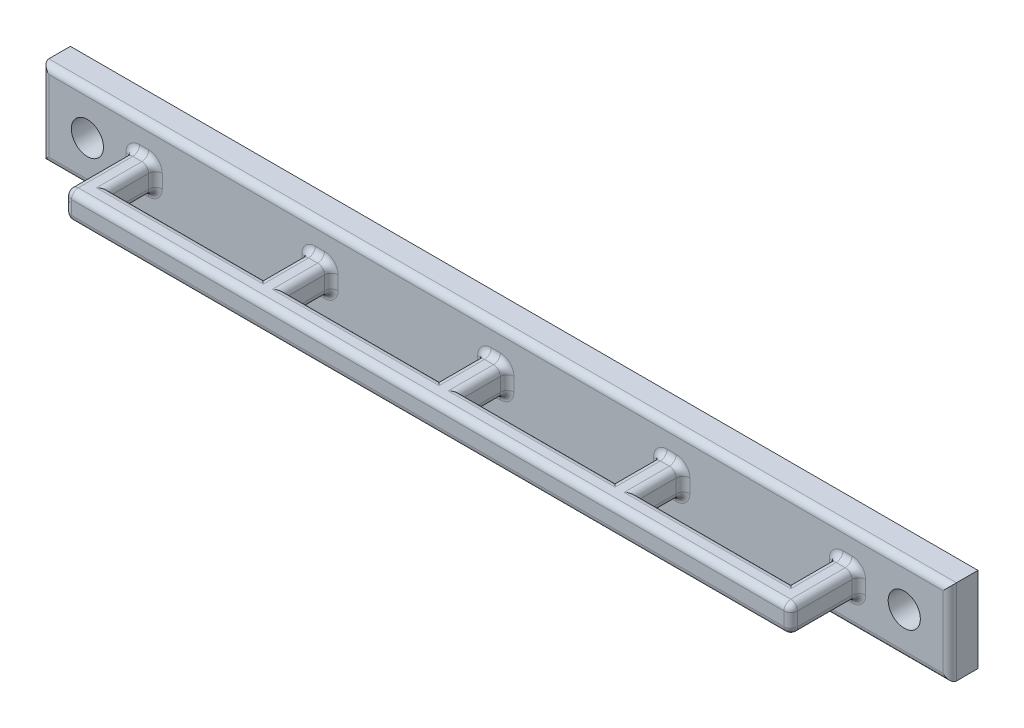
SolidWorks part; units mm, degrees
ref_plane "Front Plane" through (0, 0, 0) normal (0, 0, 1) x (1, 0, 0)
ref_plane "Top Plane" through (0, 0, 0) normal (0, 1, 0) x (1, 0, 0)
ref_plane "Right Plane" through (0, 0, 0) normal (1, 0, 0) x (0, 0, -1)
sketch "Sketch2" plane through (0, 0, 0) normal (0, 0, 1) x (1, 0, 0)
  line L1 (0, 0) -> (101.6, 0)
  line L2 (0, 0) -> (0, 9.525)
  line L3 (0, 9.525) -> (101.6, 9.525)
  line L4 (101.6, 0) -> (101.6, 9.525)
  dimension "D1" = 101.6
  dimension "D2" = 9.525
extrude "Boss-Extrude1" add sketch "Sketch2" along normal blind 3.175
hole_wizard "M3 Clearance Hole1" positions "Sketch3" profile "Sketch4" hole size "M3" standard "ANSI Metric" end condition through all
sketch "Sketch3" plane through (0, 0, 3.175) normal (0, 0, 1) x (1, 0, 0)
  line L0 (0, 9.525) -> (0, 0) construction
  line L1 (101.6, 0) -> (101.6, 9.525) construction
  line L2 (0, 0) -> (101.6, 0) construction
  point P0 (5.08, 4.7625)
  point P2 (96.52, 4.7625)
  dimension "D1" = 5.08
  dimension "D2" = 5.08
  dimension "D3" = 4.7625
sketch "Sketch4" plane through (5.08, 4.7625, 3.175) normal (1, 0, 0) x (0, -1, 0)
  line L0 (0, 0) -> (0, 3.175)
  line L1 (0, 3.175) -> (1.8, 3.175)
  line L2 (1.8, 3.175) -> (1.8, 0)
  line L5 (1.8, 0) -> (0, 0)
  line L11 (0, -6.35) -> (0, 107.95) construction
  dimension "Thru Hole Dia." = 3.6
  dimension "Thru Hole Depth" = 3.175
ref_plane "Plane1" through (0, 4.7625, 0) normal (0, -1, 0) x (-1, 0, 0)
sketch "Sketch5" plane through (0, 4.7625, 0) normal (0, -1, 0) x (-1, 0, 0)
  line L0 (-10.16, -3.175) -> (-10.16, -10.795)
  line L1 (-10.16, -10.795) -> (-91.44, -10.795)
  line L2 (-91.44, -10.795) -> (-91.44, -3.175)
  line L3 (-91.44, -3.175) -> (-88.9, -3.175)
  line L4 (-88.9, -3.175) -> (-88.9, -8.255)
  line L5 (-88.9, -8.255) -> (-71.755, -8.255)
  line L6 (-71.755, -8.255) -> (-71.755, -3.175)
  line L7 (-71.755, -3.175) -> (-69.215, -3.175)
  line L8 (-69.215, -3.175) -> (-69.215, -8.255)
  line L9 (-69.215, -8.255) -> (-52.07, -8.255)
  line L10 (-52.07, -8.255) -> (-52.07, -3.175)
  line L11 (-52.07, -3.175) -> (-49.53, -3.175)
  line L12 (-49.53, -3.175) -> (-49.53, -8.255)
  line L13 (-49.53, -8.255) -> (-32.385, -8.255)
  line L14 (-32.385, -8.255) -> (-32.385, -3.175)
  line L15 (-32.385, -3.175) -> (-29.845, -3.175)
  line L16 (-29.845, -3.175) -> (-29.845, -8.255)
  line L17 (-29.845, -8.255) -> (-12.7, -8.255)
  line L18 (-12.7, -8.255) -> (-12.7, -3.175)
  line L19 (-12.7, -3.175) -> (-10.16, -3.175)
  line L20 (-101.6, -3.175) -> (0, -3.175) construction
  line L21 (0, -3.175) -> (0, 0) construction
  line L22 (-101.6, -3.175) -> (-101.6, 0) construction
  point P2 (-11.43, -3.175)
  dimension "D1" = 10.16
  dimension "D2" = 10.16
  dimension "D3" = 5.08
  dimension "D4" = 2.54
  dimension "D5" = 2.54
extrude "Boss-Extrude2" add sketch "Sketch5" along normal blind 1.524 and the other way blind 1.524
fillet "Fillet1" radius 0.762 56 edges at (88.9, 4.7625, 3.175) (71.755, 4.7625, 3.175) (69.215, 4.7625, 3.175) (52.07, 4.7625, 3.175) (49.53, 4.7625, 3.175) (32.385, 4.7625, 3.175) (29.845, 4.7625, 3.175) (12.7, 4.7625, 3.175) (10.16, 4.7625, 10.795) (10.16, 4.7625, 3.175) (12.7, 6.2865, 5.715) (21.2725, 6.2865, 8.255) (29.845, 6.2865, 5.715) (31.115, 6.2865, 3.175) (32.385, 6.2865, 5.715) (40.9575, 6.2865, 8.255) (49.53, 6.2865, 5.715) (50.8, 6.2865, 3.175) (52.07, 6.2865, 5.715) (60.6425, 6.2865, 8.255) (69.215, 6.2865, 5.715) (70.485, 6.2865, 3.175) (71.755, 6.2865, 5.715) (80.3275, 6.2865, 8.255) (88.9, 6.2865, 5.715) (90.17, 6.2865, 3.175) (50.8, 6.2865, 10.795) (10.16, 6.2865, 6.985) (11.43, 6.2865, 3.175) (10.16, 3.2385, 6.985) (50.8, 3.2385, 10.795) (90.17, 3.2385, 3.175) (88.9, 3.2385, 5.715) (80.3275, 3.2385, 8.255) (71.755, 3.2385, 5.715) (70.485, 3.2385, 3.175) (69.215, 3.2385, 5.715) (60.6425, 3.2385, 8.255) (52.07, 3.2385, 5.715) (50.8, 3.2385, 3.175) (49.53, 3.2385, 5.715) (40.9575, 3.2385, 8.255) (32.385, 3.2385, 5.715) (31.115, 3.2385, 3.175) (29.845, 3.2385, 5.715) (21.2725, 3.2385, 8.255) (12.7, 3.2385, 5.715) (11.43, 3.2385, 3.175) (91.44, 6.2865, 6.985) (91.44, 4.7625, 3.175) (91.44, 3.2385, 6.985) (91.44, 4.7625, 10.795) (50.8, 9.525, 3.175) (101.6, 4.7625, 3.175) (50.8, 0, 3.175) (0, 4.7625, 3.175)
